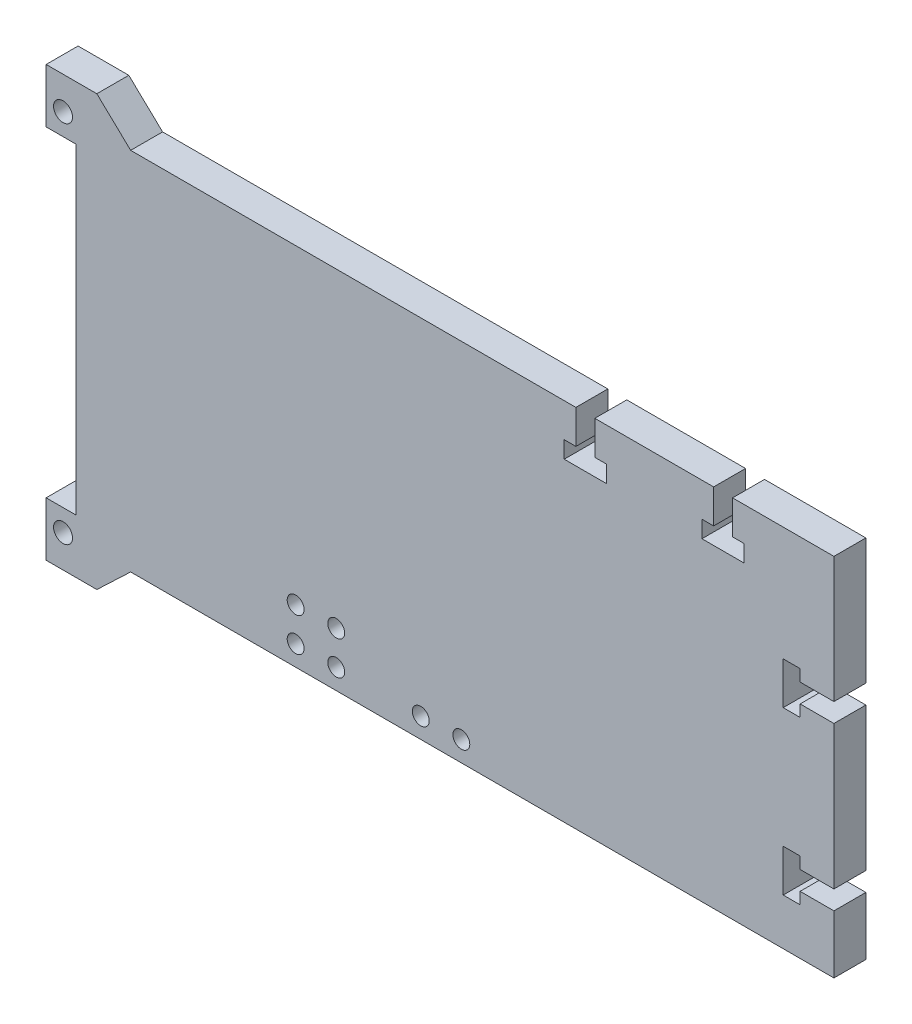
SolidWorks part; units mm, degrees
ref_plane "Front Plane" through (0, 0, 0) normal (0, 0, 1) x (1, 0, 0)
ref_plane "Top Plane" through (0, 0, 0) normal (0, 1, 0) x (1, 0, 0)
ref_plane "Right Plane" through (0, 0, 0) normal (1, 0, 0) x (0, 0, -1)
sketch "Sketch1" plane through (0, 0, 0) normal (0, 0, 1) x (1, 0, 0)
  line L1 (0, 0) -> (142.367, 0)
  line L2 (0, 0) -> (0, 68.58)
  line L3 (0, 68.58) -> (142.367, 68.58)
  line L4 (142.367, 0) -> (142.367, 68.58)
  dimension "D1" = 142.367
  dimension "D2" = 68.58
extrude "Boss-Extrude1" add sketch "Sketch1" along normal blind 6
sketch "Sketch2" plane through (0, 0, 6) normal (0, 0, 1) x (1, 0, 0)
  line L1 (0, 68.58) -> (-5.588, 68.58)
  line L2 (0, 68.58) -> (0, 64.4525)
  line L3 (0, 64.4525) -> (-5.588, 64.4525)
  line L4 (-5.588, 68.58) -> (-5.588, 64.4525)
  line L5 (0, 0) -> (-5.588, 0)
  line L6 (0, 0) -> (0, 4.1275)
  line L7 (0, 4.1275) -> (-5.588, 4.1275)
  line L8 (-5.588, 0) -> (-5.588, 4.1275)
  dimension "D1" = 5.588
  dimension "D2" = 60.325
extrude "Boss-Extrude2" add sketch "Sketch2" against normal up to surface (6 mm away) up to face at (71.1835, 34.29, 0)
sketch "Sketch3" plane through (0, 0, 6) normal (0, 0, 1) x (1, 0, 0)
  line L0 (0, 68.58) -> (0, 72.39)
  line L1 (142.367, 68.58) -> (-5.588, 68.58) construction
  line L2 (0, 72.39) -> (2.54, 72.39)
  line L3 (2.54, 72.39) -> (9.525, 68.58)
  line L4 (9.525, 68.58) -> (0, 68.58)
  line L5 (0, 0) -> (0, -3.81)
  line L6 (0, -3.81) -> (2.54, -3.81)
  line L7 (2.54, -3.81) -> (9.525, 0)
  line L8 (-5.588, 0) -> (142.367, 0) construction
  line L9 (9.525, 0) -> (0, 0)
  dimension "D1" = 3.81
  dimension "D2" = 2.54
  dimension "D3" = 9.525
extrude "Boss-Extrude3" add sketch "Sketch3" against normal up to surface (6 mm away) up to face at (32.4485, 38.0603, 0)
sketch "Sketch4" plane through (0, 0, 6) normal (0, 0, 1) x (1, 0, 0)
  line L0 (142.367, 0) -> (142.367, 68.58) construction
  line L1 (142.367, 44.958) -> (136.017, 44.958)
  line L2 (142.367, 44.958) -> (142.367, 41.402)
  line L3 (142.367, 41.402) -> (136.017, 41.402)
  line L4 (136.017, 44.958) -> (136.017, 41.402) construction
  line L5 (136.017, 44.958) -> (136.017, 47.1487)
  line L6 (142.367, 14.478) -> (136.017, 14.478)
  line L7 (142.367, 14.478) -> (142.367, 10.922)
  line L8 (142.367, 10.922) -> (136.017, 10.922)
  line L9 (136.017, 14.478) -> (136.017, 10.922) construction
  line L10 (136.017, 47.1487) -> (132.842, 47.1487)
  line L11 (132.842, 47.1487) -> (132.842, 39.2112)
  line L12 (132.842, 39.2112) -> (136.017, 39.2112)
  line L13 (136.017, 39.2112) -> (136.017, 41.402)
  line L14 (136.017, 14.478) -> (136.017, 16.6688)
  line L15 (136.017, 16.6688) -> (132.842, 16.6688)
  line L16 (132.842, 16.6688) -> (132.842, 8.7313)
  line L17 (132.842, 8.7313) -> (136.017, 8.7313)
  line L18 (136.017, 8.7313) -> (136.017, 10.922)
  line L19 (132.842, 43.18) -> (142.367, 43.18) construction
  line L20 (132.842, 12.7) -> (142.367, 12.7) construction
  line L21 (142.367, 68.58) -> (9.525, 68.58) construction
  line L22 (9.525, 0) -> (142.367, 0) construction
  line L23 (93.9038, 62.23) -> (91.713, 62.23)
  line L24 (123.3322, 68.58) -> (119.7762, 68.58)
  line L25 (123.3322, 68.58) -> (123.3322, 62.23)
  line L26 (123.3322, 62.23) -> (119.7762, 62.23) construction
  line L27 (119.7762, 68.58) -> (119.7762, 62.23)
  line L28 (97.4598, 68.58) -> (93.9038, 68.58)
  line L29 (97.4598, 68.58) -> (97.4598, 62.23)
  line L30 (97.4598, 62.23) -> (93.9038, 62.23) construction
  line L31 (93.9038, 68.58) -> (93.9038, 62.23)
  line L32 (91.713, 62.23) -> (91.713, 59.055)
  line L33 (91.713, 59.055) -> (99.6505, 59.055)
  line L34 (99.6505, 59.055) -> (99.6505, 62.23)
  line L35 (99.6505, 62.23) -> (97.4598, 62.23)
  line L36 (119.7762, 62.23) -> (117.5855, 62.23)
  line L37 (117.5855, 62.23) -> (117.5855, 59.055)
  line L38 (117.5855, 59.055) -> (125.523, 59.055)
  line L39 (125.523, 59.055) -> (125.523, 62.23)
  line L40 (125.523, 62.23) -> (123.3322, 62.23)
  line L41 (95.6818, 59.055) -> (95.6818, 68.58) construction
  line L42 (121.5542, 59.055) -> (121.5542, 68.58) construction
  dimension "D1" = 25.4
  dimension "D2" = 12.7
  dimension "D3" = 7.9375
  dimension "D4" = 3.175
  dimension "D5" = 6.35
  dimension "D6" = 3.556
  dimension "D7" = 20.8128
  dimension "D8" = 46.6852
extrude "Cut-Extrude1" cut sketch "Sketch4" against normal through all
sketch "Sketch5" plane through (0, 0, 6) normal (0, 0, 1) x (1, 0, 0)
  line L0 (10.287, 0) -> (3.937, -6.0325)
  line L1 (-5.588, 68.58) -> (10.287, 68.58)
  line L2 (-5.588, 68.58) -> (-5.588, 74.6125)
  line L3 (-5.588, 74.6125) -> (10.287, 74.6125) construction
  line L4 (10.287, 68.58) -> (10.287, 74.6125) construction
  line L5 (-5.588, 0) -> (10.287, 0)
  line L6 (-5.588, 0) -> (-5.588, -6.0325)
  line L7 (-5.588, -6.0325) -> (10.287, -6.0325) construction
  line L8 (10.287, 0) -> (10.287, -6.0325) construction
  line L9 (3.937, -6.0325) -> (-5.588, -6.0325)
  line L10 (10.287, 68.58) -> (3.937, 74.6125)
  line L11 (3.937, 74.6125) -> (-5.588, 74.6125)
  dimension "D1" = 80.645
  dimension "D2" = 15.875
  dimension "D3" = 9.525
extrude "Boss-Extrude4" add sketch "Sketch5" against normal up to surface (6 mm away) up to face at (87.6463, 42.3796, 0)
sketch "Sketch6" plane through (0, 0, 6) normal (0, 0, 1) x (1, 0, 0)
  line L0 (-5.588, 68.5165) -> (-2.413, 68.5165) construction
  line L1 (41.275, 3.81) -> (41.275, 10.16) construction
  line L2 (-5.588, 0.0635) -> (-2.413, 0.0635) construction
  line L3 (41.275, 10.16) -> (48.895, 10.16) construction
  line L4 (48.895, 3.81) -> (64.77, 3.81) construction
  line L5 (64.77, 3.81) -> (72.39, 3.81) construction
  line L6 (10.287, 0) -> (142.367, 0) construction
  line L7 (41.275, 3.81) -> (48.895, 3.81) construction
  line L8 (48.895, 10.16) -> (48.895, 3.81) construction
  line L9 (-5.588, 64.4525) -> (0, 64.4525) construction
  line L10 (0, 4.1275) -> (-5.588, 4.1275) construction
  line L11 (-5.588, 74.6125) -> (-5.588, 64.4525) construction
  line L12 (-5.588, 4.1275) -> (-5.588, -6.0325) construction
  circle A0 centre (-2.413, 68.5165) radius 1.778
  circle A1 centre (-2.413, 0.0635) radius 1.778
  circle A2 centre (64.77, 3.81) radius 1.5875
  circle A3 centre (72.39, 3.81) radius 1.5875
  circle A4 centre (41.275, 3.81) radius 1.5875
  circle A5 centre (48.895, 3.81) radius 1.5875
  circle A6 centre (41.275, 10.16) radius 1.5875
  circle A7 centre (48.895, 10.16) radius 1.5875
  dimension "D1" = 3.556
  dimension "D4" = 15.875
  dimension "D3" = 3.175
  dimension "D2" = 3.175
  dimension "D5" = 41.275
  dimension "D6" = 3.81
  dimension "D7" = 7.62
  dimension "D8" = 4.064
  dimension "D9" = 4.064
  dimension "D10" = 6.35
extrude "Cut-Extrude2" cut sketch "Sketch6" against normal through all
sketch "Sketch7" plane through (0, 0, 6) normal (0, 0, 1) x (1, 0, 0)
  line L0 (119.7762, 68.58) -> (97.4598, 68.58) construction
  line L1 (91.713, 59.055) -> (99.6505, 59.055)
  line L2 (91.713, 59.055) -> (91.713, 68.58)
  line L3 (91.713, 68.58) -> (99.6505, 68.58) construction
  line L4 (99.6505, 59.055) -> (99.6505, 68.58)
  line L5 (142.367, 68.58) -> (123.3322, 68.58) construction
  line L6 (117.5855, 59.055) -> (125.523, 59.055)
  line L7 (117.5855, 59.055) -> (117.5855, 68.58)
  line L8 (117.5855, 68.58) -> (125.523, 68.58) construction
  line L9 (125.523, 59.055) -> (125.523, 68.58)
  line L10 (142.367, 44.958) -> (142.367, 68.58) construction
  line L11 (132.842, 39.2112) -> (142.367, 39.2112)
  line L12 (132.842, 39.2112) -> (132.842, 47.1487) construction
  line L13 (132.842, 47.1487) -> (142.367, 47.1487)
  line L14 (142.367, 39.2112) -> (142.367, 47.1487) construction
  line L15 (142.367, 14.478) -> (142.367, 41.402) construction
  line L16 (132.842, 8.7313) -> (142.367, 8.7313)
  line L17 (132.842, 8.7313) -> (132.842, 16.6688) construction
  line L18 (132.842, 16.6688) -> (142.367, 16.6688)
  line L19 (142.367, 8.7313) -> (142.367, 16.6688) construction
  line L20 (136.017, 47.1487) -> (132.842, 47.1487) construction
  line L21 (136.017, 16.6688) -> (132.842, 16.6688) construction
  line L22 (125.523, 59.055) -> (125.523, 62.23) construction
  line L23 (99.6505, 59.055) -> (99.6505, 62.23) construction
  line L24 (132.842, 12.7) -> (142.367, 12.7) construction
  line L25 (94.1832, 68.58) -> (97.1804, 68.58) construction
  line L26 (94.1832, 68.58) -> (94.1832, 62.23)
  line L27 (94.1832, 62.23) -> (97.1804, 62.23)
  line L28 (97.1804, 68.58) -> (97.1804, 62.23)
  line L29 (120.0556, 68.58) -> (123.0528, 68.58) construction
  line L30 (120.0556, 68.58) -> (120.0556, 62.23)
  line L31 (120.0556, 62.23) -> (123.0528, 62.23)
  line L32 (123.0528, 68.58) -> (123.0528, 62.23)
  line L33 (142.367, 44.6786) -> (132.842, 44.6786)
  line L34 (142.367, 44.6786) -> (142.367, 41.6814) construction
  line L35 (142.367, 41.6814) -> (132.842, 41.6814)
  line L36 (132.842, 44.6786) -> (132.842, 41.6814) construction
  line L37 (142.367, 14.1986) -> (132.842, 14.1986)
  line L38 (142.367, 14.1986) -> (142.367, 11.2014) construction
  line L39 (142.367, 11.2014) -> (132.842, 11.2014)
  line L40 (132.842, 14.1986) -> (132.842, 11.2014) construction
  line L41 (132.842, 43.18) -> (142.367, 43.18) construction
  line L42 (95.6818, 62.23) -> (95.6818, 68.58) construction
  line L43 (121.5542, 62.23) -> (121.5542, 68.58) construction
  line L44 (91.713, 68.58) -> (94.1832, 68.58)
  line L45 (97.1804, 68.58) -> (99.6505, 68.58)
  line L46 (117.5855, 68.58) -> (120.0556, 68.58)
  line L47 (123.0528, 68.58) -> (125.523, 68.58)
  line L48 (142.367, 47.1487) -> (142.367, 44.6786)
  line L49 (142.367, 41.6814) -> (142.367, 39.2112)
  line L50 (142.367, 16.6688) -> (142.367, 14.1986)
  line L51 (142.367, 11.2014) -> (142.367, 8.7313)
  line L52 (132.842, 44.6786) -> (132.842, 47.1487)
  line L53 (132.842, 41.6814) -> (132.842, 39.2112)
  line L54 (132.842, 16.6688) -> (132.842, 14.1986)
  line L55 (132.842, 11.2014) -> (132.842, 8.7313)
  dimension "D1" = 2.9972
  dimension "D2" = 6.35
  dimension "D3" = 9.525
extrude "Boss-Extrude5" [suppressed] add sketch "Sketch7" against normal up to surface (6 mm away)
chamfer "Chamfer1" [suppressed] distance 0.381 angle 70
fillet "Fillet1" [suppressed] radius 0.508
